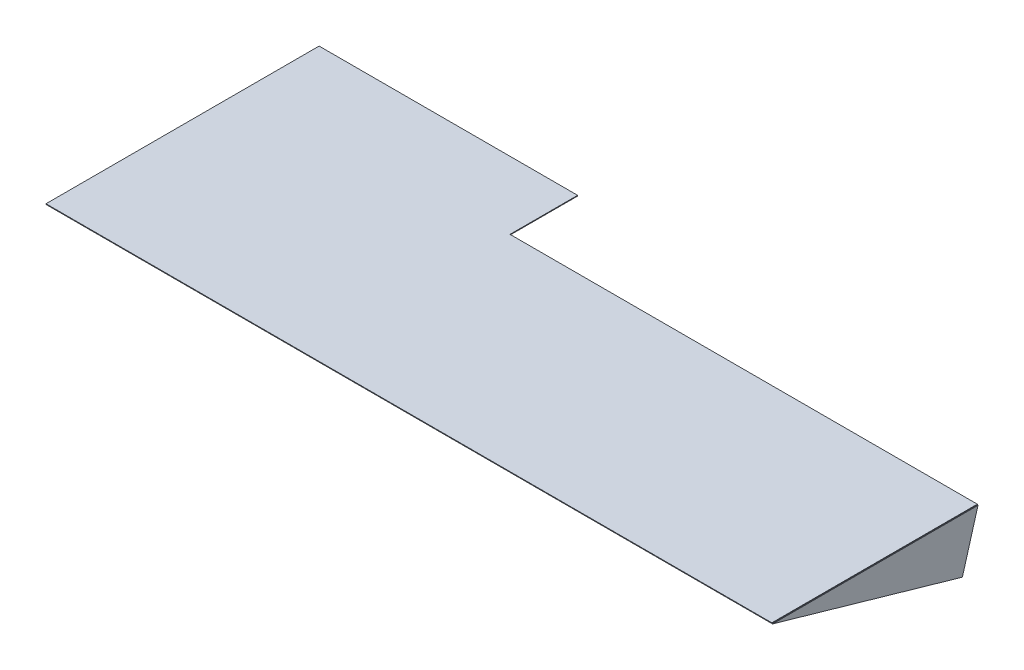
SolidWorks part; units mm, degrees
ref_plane "Спереди" through (0, 0, 0) normal (0, 0, 1) x (1, 0, 0)
ref_plane "Сверху" through (0, 0, 0) normal (0, 1, 0) x (1, 0, 0)
ref_plane "Справа" through (0, 0, 0) normal (1, 0, 0) x (0, 0, -1)
sketch "Эскиз1" plane through (0, 0, 0) normal (0, 1, 0) x (1, 0, 0)
  line L1 (0, 0) -> (10950, 0)
  line L2 (0, 0) -> (0, 4120)
  line L3 (3900, 3100) -> (10950, 3100)
  line L4 (10950, 0) -> (10950, 3100)
  line L6 (3900, 3100) -> (3900, 4120)
  line L7 (3900, 4120) -> (0, 4120)
  point P8 (0, 0)
  dimension "D1" = 7050
  dimension "D2" = 3900
  dimension "D3" = 3100
  dimension "D4" = 4120
extrude "Бобышка-Вытянуть1" add sketch "Эскиз1" along normal blind 10
sketch "Эскиз2" plane through (10950, 0, 0) normal (1, 0, 0) x (0, 0, -1)
  line L0 (0, 0) -> (2864.4745, -821.3749)
  line L1 (2864.4745, -821.3749) -> (3100, 0)
  line L2 (0, 0) -> (3100, 0) construction
  line L3 (0, 0) -> (3100, 0)
  dimension "D1" = 16
extrude "Бобышка-Вытянуть2" add sketch "Эскиз2" along normal blind 10 separate body
